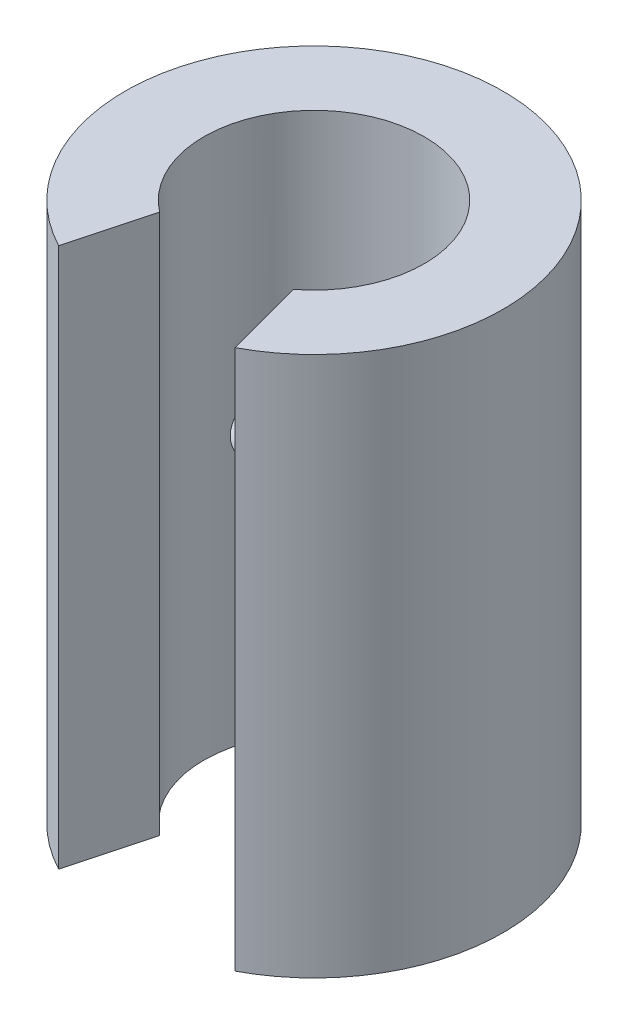
SolidWorks part; units mm, degrees
ref_plane "Front Plane" through (0, 0, 0) normal (0, 0, 1) x (1, 0, 0)
ref_plane "Top Plane" through (0, 0, 0) normal (0, 1, 0) x (1, 0, 0)
ref_plane "Right Plane" through (0, 0, 0) normal (1, 0, 0) x (0, 0, -1)
sketch "Sketch1" plane through (0, 0, 0) normal (0, 1, 0) x (1, 0, 0)
  circle A0 centre (0, 0) radius 11.1125
  dimension "D1" = 22.225
extrude "Boss-Extrude1" add sketch "Sketch1" along normal blind 31.75
sketch "Sketch2" plane through (0, 31.75, 0) normal (0, 1, 0) x (1, 0, 0)
  line L0 (-3.937, -5.1431) -> (-5.1916, -9.8252)
  line L1 (3.937, -5.1431) -> (5.1916, -9.8252)
  line L2 (-3.937, -5.1431) -> (-3.937, -10.3917) construction
  line L3 (3.937, -5.1431) -> (3.937, -10.3917) construction
  line L4 (-3.937, -5.1431) -> (3.937, -5.1431) construction
  arc A0 (3.937, -5.1431) -> (-3.937, -5.1431) centre (0, 0) ccw
  circle A2 centre (0, 0) radius 11.1125 construction
  arc A3 (-5.1916, -9.8252) -> (5.1916, -9.8252) centre (0, 0) ccw
  point P3 (-3.937, -5.1431)
  point P8 (3.937, -5.1431)
  dimension "D1" = 12.954
  dimension "D2" = 15
  dimension "D3" = 15
  dimension "D4" = 7.874
extrude "Cut-Extrude1" cut sketch "Sketch2" against normal through all
sketch "Sketch3" plane through (0, 0, 0) normal (1, 0, 0) x (0, 0, -1)
  line L0 (0, 31.75) -> (0, 0) construction
  line L3 (0, 15.875) -> (3.175, 15.875) construction
  line L4 (6.477, 31.75) -> (-5.1431, 31.75) construction
  circle A0 centre (3.175, 15.875) radius 1.778
  point P2 (0, 0)
  point P6 (0, 15.875)
  dimension "D2" = 3.556
  dimension "D1" = 3.175
extrude "Cut-Extrude2" cut sketch "Sketch3" against normal blind 31.75
